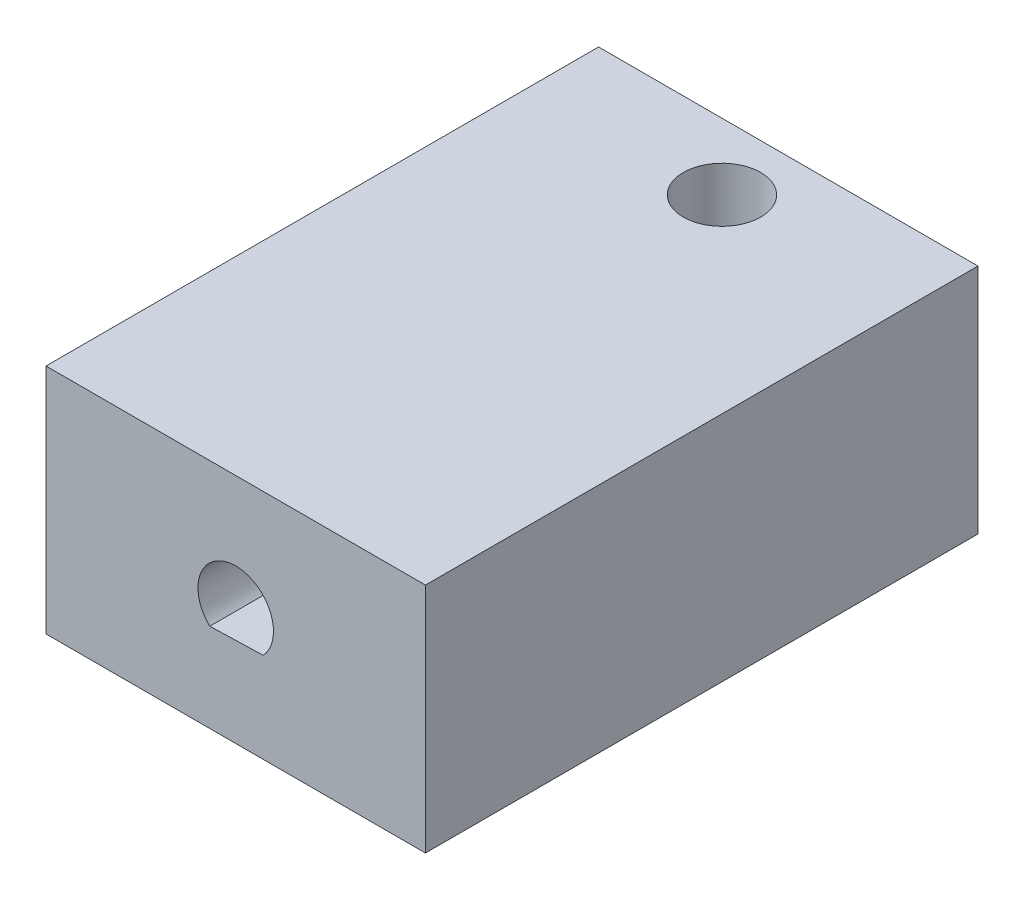
SolidWorks part; units mm, degrees
ref_plane "Front" through (0, 0, 0) normal (0, 0, 1) x (1, 0, 0)
ref_plane "Top" through (0, 0, 0) normal (0, 1, 0) x (1, 0, 0)
ref_plane "Right" through (0, 0, 0) normal (1, 0, 0) x (0, 0, -1)
sketch "Эскиз2" plane through (0, 0, 0) normal (0, 0, 1) x (1, 0, 0)
  line L1 (-10.3, 6.3) -> (10.3, 6.3)
  line L2 (-10.3, 6.3) -> (-10.3, -6.3)
  line L3 (-10.3, -6.3) -> (10.3, -6.3)
  line L4 (10.3, 6.3) -> (10.3, -6.3)
  line L5 (-10.3, 6.3) -> (10.3, -6.3) construction
  line L6 (-10.3, -6.3) -> (10.3, 6.3) construction
  point P0 (0, 0)
  dimension "D1" = 12.6
  dimension "D2" = 20.6
extrude "Бобышка-Вытянуть1" add sketch "Эскиз2" along normal blind 30
sketch "Эскиз3" plane through (0, 0, 30) normal (0, 0, 1) x (1, 0, 0)
  line L0 (-1.4082, -1.4898) -> (1.489, -1.409)
  arc A0 (-1.4082, -1.4898) -> (1.489, -1.409) centre (0, 0) cw
  point P4 (-0.0571, 2.0492)
  dimension "D1" = 2.05
  dimension "D2" = 3.5
extrude "Вырез-Вытянуть1" cut sketch "Эскиз3" against normal blind 30
sketch "Эскиз4" plane through (0, -6.3, 0) normal (0, -1, 0) x (1, 0, 0)
  line L0 (10.3, 0) -> (-10.3, 7.2) construction
  line L1 (10.3, 0) -> (-10.3, 0) construction
  line L2 (10.3, 0) -> (10.3, 30) construction
  line L3 (10.3, 30) -> (-10.3, 30) construction
  line L4 (-10.3, 0) -> (-10.3, 30) construction
  line L5 (10.3, 0) -> (-10.3, 0) construction
  line L6 (10.3, 0) -> (10.3, 7.2) construction
  line L7 (10.3, 7.2) -> (-10.3, 7.2) construction
  line L8 (-10.3, 0) -> (-10.3, 7.2) construction
  line L9 (-10.3, 0) -> (10.3, 7.2) construction
  circle A0 centre (0, 3.6) radius 2.1
  point P10 (0, 0)
  dimension "D2" = 4.2
  dimension "D1" = 7.2
extrude "Вырез-Вытянуть3" cut sketch "Эскиз4" against normal blind 6 contours A0
sketch "Эскиз5" plane through (0, -6.3, 0) normal (0, -1, 0) x (1, 0, 0)
sketch "Эскиз6" plane through (0, -6.3, 0) normal (0, -1, 0) x (1, 0, 0)
  line L0 (10.3, 30) -> (10.3, 0) construction
  line L1 (-10.3, 0) -> (10.3, 0) construction
  line L2 (-10.3, 0) -> (-10.3, 7.2) construction
  line L3 (-10.3, 7.2) -> (10.3, 7.2) construction
  line L4 (10.3, 0) -> (10.3, 7.2) construction
  line L5 (-10.3, 0) -> (10.3, 7.2) construction
  line L6 (-10.3, 7.2) -> (10.3, 0) construction
  circle A0 centre (0, 3.6) radius 2.1
  dimension "D1" = 7.2
extrude "Вырез-Вытянуть4" cut sketch "Эскиз6" against normal blind 30
